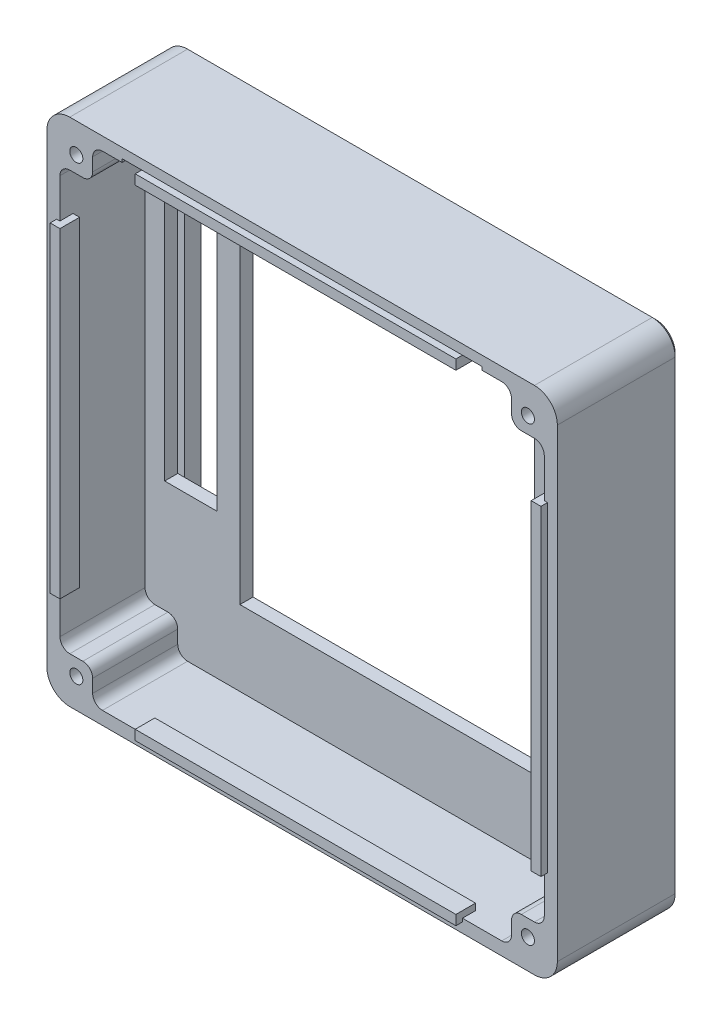
SolidWorks part; units mm, degrees
ref_plane "前视基准面" through (0, 0, 0) normal (0, 0, 1) x (1, 0, 0)
ref_plane "上视基准面" through (0, 0, 0) normal (0, 1, 0) x (1, 0, 0)
ref_plane "右视基准面" through (0, 0, 0) normal (1, 0, 0) x (0, 0, -1)
other "Configuration Table"
sketch "草图1" plane through (0, 0, 0) normal (0, 0, 1) x (1, 0, 0)
  line L1 (-39, -39) -> (39, -39)
  line L2 (-39, -39) -> (-39, 39)
  line L3 (-39, 39) -> (39, 39)
  line L4 (39, -39) -> (39, 39)
  line L5 (-39, -39) -> (39, 39) construction
  line L6 (-39, 39) -> (39, -39) construction
  point P0 (0, 0)
  dimension "D1" = 78
extrude "凸台-拉伸1" add sketch "草图1" along normal blind 5.5
sketch "草图2" plane through (0, 0, 5.5) normal (0, 0, 1) x (1, 0, 0)
  line L1 (-39, -39) -> (39, -39)
  line L2 (-39, -39) -> (-39, 39)
  line L3 (-39, 39) -> (39, 39)
  line L4 (39, -39) -> (39, 39)
  line L5 (-39, -39) -> (39, 39) construction
  line L6 (-39, 39) -> (39, -39) construction
  line L7 (37, 37) -> (-37, 37)
  line L8 (37, 37) -> (37, -37)
  line L9 (37, -37) -> (-37, -37)
  line L10 (-37, 37) -> (-37, -37)
  line L11 (37, 37) -> (-37, -37) construction
  line L12 (37, -37) -> (-37, 37) construction
  line L13 (-37, 37) -> (-32, 37)
  line L14 (-37, 37) -> (-37, 32)
  line L15 (-37, 32) -> (-32, 32)
  line L16 (-32, 37) -> (-32, 32)
  line L17 (37, 37) -> (32, 37)
  line L18 (37, 37) -> (37, 32)
  line L19 (37, 32) -> (32, 32)
  line L20 (32, 37) -> (32, 32)
  line L21 (-37, -37) -> (-32, -37)
  line L22 (-37, -37) -> (-37, -32)
  line L23 (-37, -32) -> (-32, -32)
  line L24 (-32, -37) -> (-32, -32)
  line L25 (37, -37) -> (32, -37)
  line L26 (37, -37) -> (37, -32)
  line L27 (37, -32) -> (32, -32)
  line L28 (32, -37) -> (32, -32)
  point P0 (0, 0)
  point P7 (0, 0)
  line M22 (39, -39) -> (39, 39)
  line M23 (39, 39) -> (-39, 39)
  line M24 (-39, 39) -> (-39, -39)
  line M25 (-39, -39) -> (39, -39)
  dimension "D1" = 2
  dimension "D2" = 5
extrude "凸台-拉伸2" add sketch "草图2" along normal blind 13 contours L10 L7 L8 L9 M25 M22 M23 M24 | L16 L7 L10 L15 | L7 L20 L19 L8 | L28 L9 L8 L27 | L9 L24 L23 L10
fillet "圆角1" radius 1.5 12 edges at (37, 32, 12) (32, 32, 12) (32, 37, 12) (37, -32, 12) (32, -32, 12) (32, -37, 12) (-32, -37, 12) (-32, -32, 12) (-37, -32, 12) (-37, 32, 12) (-32, 37, 12) (-32, 32, 12)
fillet "圆角2" radius 3.5 4 edges at (-39, 39, 9.25) (39, 39, 9.25) (39, -39, 9.25) (-39, -39, 9.25)
sketch "草图3" plane through (0, 0, 0) normal (0, 0, -1) x (-1, 0, 0)
  line L8 (37.5, -35.5) -> (37.5, 35.5)
  line L9 (-35.5, -37.5) -> (35.5, -37.5)
  line L10 (-37.5, 35.5) -> (-37.5, -35.5)
  line L11 (35.5, 37.5) -> (-35.5, 37.5)
  line L12 (37.5, -35.5) -> (37.5, 35.5)
  line L13 (-35.5, -37.5) -> (35.5, -37.5)
  line L14 (-37.5, 35.5) -> (-37.5, -35.5)
  line L15 (35.5, 37.5) -> (-35.5, 37.5)
  arc A8 (37.5, 35.5) -> (35.5, 37.5) centre (35.5, 35.5) ccw
  arc A9 (35.5, -37.5) -> (37.5, -35.5) centre (35.5, -35.5) ccw
  arc A10 (-37.5, -35.5) -> (-35.5, -37.5) centre (-35.5, -35.5) ccw
  arc A11 (-35.5, 37.5) -> (-37.5, 35.5) centre (-35.5, 35.5) ccw
  arc A12 (37.5, 35.5) -> (35.5, 37.5) centre (35.5, 35.5) ccw
  arc A13 (35.5, -37.5) -> (37.5, -35.5) centre (35.5, -35.5) ccw
  arc A14 (-37.5, -35.5) -> (-35.5, -37.5) centre (-35.5, -35.5) ccw
  arc A15 (-35.5, 37.5) -> (-37.5, 35.5) centre (-35.5, 35.5) ccw
  dimension "D1" = 1.5
extrude "切除-拉伸1" cut sketch "草图3" against normal blind 1
sketch "草图4" plane through (0, 0, 1) normal (0, 0, -1) x (-1, 0, 0)
  line L0 (35.5, 37.5) -> (-35.5, 37.5) construction
  line L1 (-32.95, 37.5) -> (32.95, 37.5)
  line L2 (-32.95, 37.5) -> (-32.95, -33)
  line L3 (-32.95, -33) -> (32.95, -33)
  line L4 (32.95, 37.5) -> (32.95, -33)
  line L6 (0, 0) -> (0, 26.6317) construction
  line L7 (-32.95, 36.85) -> (32.95, 36.85)
  line L8 (27.5, 36.85) -> (27.5, 37.5)
  line L9 (-27.5, 36.85) -> (-27.5, 37.5)
  line M10 (35.5, 37.5) -> (-35.5, 37.5)
  dimension "D1" = 70.5
  dimension "D2" = 65.9
  dimension "D3" = 0.65
  dimension "D4" = 55
extrude "切除-拉伸2" cut sketch "草图4" against normal blind 2.5 contours L3 L6 L7 L2 | L6 L3 L4 L7 | L7 L6 L9 M10 | L6 L7 L8 L1
sketch "草图5" plane through (0, 0, 1) normal (0, 0, -1) x (-1, 0, 0)
  line L0 (-35.5, 39) -> (35.5, 39) construction
  line L1 (-34.5, -34.5) -> (34.5, -34.5) construction
  line L2 (-34.5, -34.5) -> (-34.5, 34.5) construction
  line L3 (-34.5, 34.5) -> (34.5, 34.5) construction
  line L4 (34.5, -34.5) -> (34.5, 34.5) construction
  line L5 (-34.5, -34.5) -> (34.5, 34.5) construction
  line L6 (-34.5, 34.5) -> (34.5, -34.5) construction
  circle A0 centre (-34.5, 34.5) radius 1
  circle A1 centre (34.5, 34.5) radius 1
  circle A2 centre (34.5, -34.5) radius 1
  circle A3 centre (-34.5, -34.5) radius 1
  point P0 (0, 0)
  dimension "D2" = 2
  dimension "D1" = 4.5
extrude "切除-拉伸3" cut sketch "草图5" against normal through all
chamfer "倒角1" distance 0.5 angle 45 8 edges at (-39, 0, 0) (-37.9749, -37.9749, 0) (-37.9749, 37.9749, 0) (0, -39, 0) (0, 39, 0) (37.9749, -37.9749, 0) (37.9749, 37.9749, 0) (39, 0, 0)
sketch "草图6" plane through (0, 0, 3.5) normal (0, 0, -1) x (-1, 0, 0)
  line L1 (-27.5, 37.5) -> (27.5, 37.5)
  line L2 (-27.5, 37.5) -> (-27.5, 35.5)
  line L3 (-27.5, 35.5) -> (27.5, 35.5)
  line L4 (27.5, 37.5) -> (27.5, 35.5)
  line L5 (-22.5, 29.5) -> (22.5, 29.5)
  line L6 (-22.5, 29.5) -> (-22.5, -25.5)
  line L7 (-22.5, -25.5) -> (22.5, -25.5)
  line L8 (22.5, 29.5) -> (22.5, -25.5)
  line L9 (26, 27.1) -> (34, 27.1)
  line L10 (26, 27.1) -> (26, -14.9)
  line L11 (26, -14.9) -> (34, -14.9)
  line L12 (34, 27.1) -> (34, -14.9)
  dimension "D1" = 2
  dimension "D2" = 45
  dimension "D3" = 25.5
  dimension "D4" = 55
  dimension "D5" = 22.5
  dimension "D6" = 26
  dimension "D7" = 8
  dimension "D8" = 42
  dimension "D9" = 14.9
extrude "切除-拉伸4" cut sketch "草图6" against normal through all
sketch "草图7" plane through (0, 0, 18.5) normal (0, 0, 1) x (1, 0, 0)
  line L0 (-15.0283, 0) -> (15.498, 0) construction
  line L1 (-24.5, 37.5) -> (24.5, 37.5)
  line L2 (-24.5, 37.5) -> (-24.5, 36)
  line L3 (-24.5, 36) -> (24.5, 36)
  line L4 (24.5, 37.5) -> (24.5, 36)
  line L5 (-37.5, 24.5) -> (-36, 24.5)
  line L6 (-37.5, 24.5) -> (-37.5, -24.5)
  line L7 (-37.5, -24.5) -> (-36, -24.5)
  line L8 (-36, 24.5) -> (-36, -24.5)
  line L9 (-24.5, -37.5) -> (24.5, -37.5)
  line L10 (-24.5, -37.5) -> (-24.5, -36)
  line L11 (-24.5, -36) -> (24.5, -36)
  line L12 (24.5, -37.5) -> (24.5, -36)
  line L13 (37.5, -24.5) -> (36, -24.5)
  line L14 (37.5, -24.5) -> (37.5, 24.5)
  line L15 (37.5, 24.5) -> (36, 24.5)
  line L16 (36, -24.5) -> (36, 24.5)
  line L17 (0, -8.9343) -> (0, 15.7561) construction
  line L18 (-37, 30.5) -> (-37, -30.5) construction
  line L19 (30.5, -37) -> (-30.5, -37) construction
  dimension "D1" = 49
  dimension "D2" = 1.5
  dimension "D3" = 0.5
  dimension "D4" = 0.5
extrude "凸台-拉伸3" add sketch "草图7" along normal blind 1 and the other way blind 2
